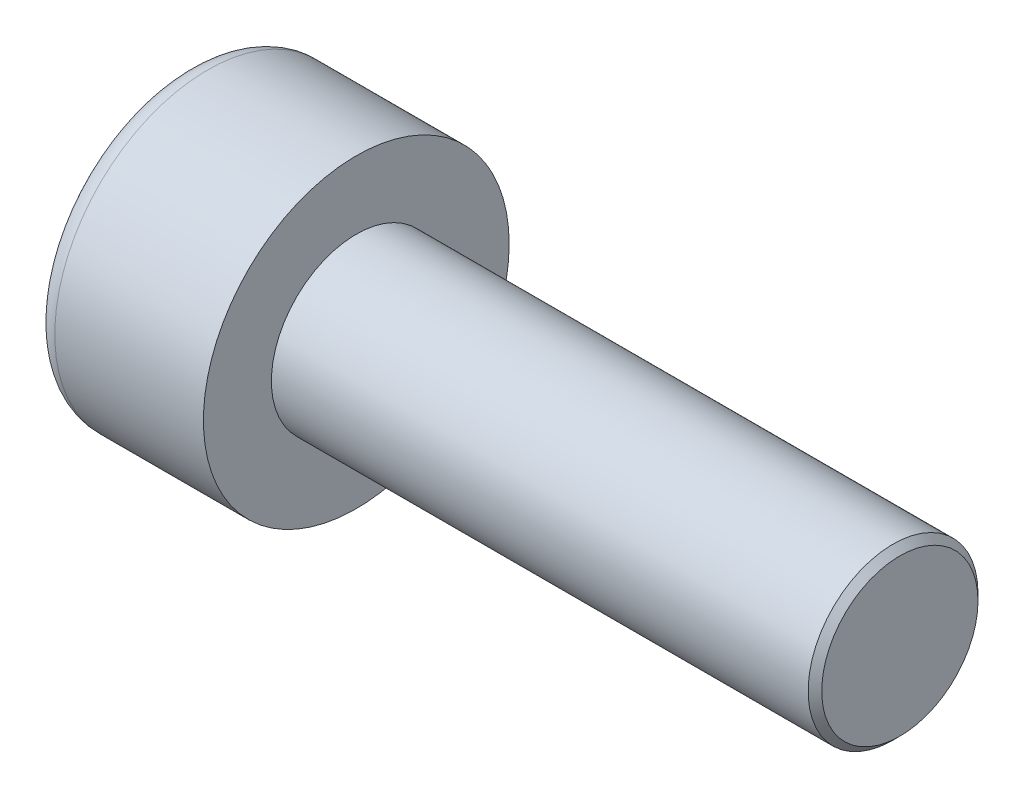
SolidWorks part; units mm, degrees
ref_plane "Front" through (0, 0, 0) normal (0, 0, 1) x (1, 0, 0)
ref_plane "Top" through (0, 0, 0) normal (0, 1, 0) x (1, 0, 0)
ref_plane "Right" through (0, 0, 0) normal (1, 0, 0) x (0, 0, -1)
sketch "Sketch1" plane through (0, 0, 0) normal (1, 0, 0) x (0, 0, -1)
  circle A0 centre (0, 0) radius 2.25
  dimension "dk" = 4.5
extrude "BaseHead" add sketch "Sketch1" along normal blind 2.5
sketch "Sketch2" plane through (2.5, 0, 0) normal (1, 0, 0) x (0, 0, -1)
  circle A0 centre (0, 0) radius 1.25
  dimension "d" = 2.5
extrude "BaseBody" add sketch "Sketch2" along normal blind 8
cosmetic thread "ThreadCosmetic1" [suppressed] parameters "b"=8, "D2"=2.013
sketch "Sketch3" plane through (0, 0, 0) normal (1, 0, 0) x (0, 0, -1)
  line L1 (1.1547, 0) -> (0.5774, 1)
  line L2 (0.5774, 1) -> (-0.5774, 1)
  line L3 (-0.5774, 1) -> (-1.1547, 0)
  line L4 (-1.1547, 0) -> (-0.5774, -1)
  line L5 (-0.5774, -1) -> (0.5774, -1)
  line L6 (0.5774, -1) -> (1.1547, 0)
  circle A0 centre (0, 0) radius 1 construction
  dimension "s" = 2
  dimension "e" = 2.3094
extrude "HexagonSocket" cut sketch "Sketch3" along normal blind 1.1
sketch "Sketch4" plane through (-4.1961, 0.75, 0) normal (0, 0, 1) x (-1, 0, 0)
  line L0 (-5.2961, 1.75) -> (-5.8735, 0.75)
  line L2 (-5.8735, 0.75) -> (-5.2961, 0.75)
  line L3 (-5.2961, 0.75) -> (-5.2961, 1.75)
  line L4 (-5.0351, 0.75) -> (0.839, 0.75) construction
  line L5 (-14.6961, 0.75) -> (-6.6961, 0.75) construction
  line L6 (-6.6961, 0.75) -> (-4.1961, 0.75) construction
  dimension "m" = 60
revolve "Cut-Revolve1" cut sketch "Sketch4" angle 360 about L4
fillet "HeadFillet" [suppressed] radius 0.1
fillet "TopFillet" radius 0.3125 1 edges at (0, 0, -2.25)
chamfer "Chamfer1" distance 0.1 angle 45 1 edges at (10.5, 0, -1.25)
sketch "Sketch5" plane through (0, 0, 0) normal (0, 0, 1) x (1, 0, 0)
  line L0 (10.4, 1.0391) -> (10.5217, 1.25)
  line L1 (10.5217, 1.25) -> (10.5217, 1.4935)
  line L2 (10.5217, 1.4935) -> (10.2782, 1.4935)
  line L3 (10.2782, 1.4935) -> (10.2782, 1.25)
  line L4 (10.2782, 1.25) -> (10.4, 1.0391)
  line L5 (0, 0) -> (7.8886, 0) construction
  line L6 (10.4, -1.25) -> (10.4, 1.25) construction
  dimension "D1" = 2.5
  dimension "D2" = 0.2435
revolve "Cut-Revolve10" [suppressed] cut sketch "Sketch5" angle 360 about L5
pattern_linear "LPattern10" [suppressed] count 27 spacing 0.2922 along (1, 0, 0)
equation "\"r1@TopFillet\" = \"d@Sketch2\" / 8"
equation "\"D1@Chamfer1\" = \"r@HeadFillet\""
equation "\"D1@Sketch5\" = \"d@Sketch2\""
equation "\"D2@Sketch5\" =  ( \"d@Sketch2\" - \"D2@ThreadCosmetic1\" )  / 2"
equation "\"D3@LPattern10\" = \"D2@Sketch5\" * 1.2"
equation "\"D1@LPattern10\" = \"b@ThreadCosmetic1\" / \"D3@LPattern10\""
